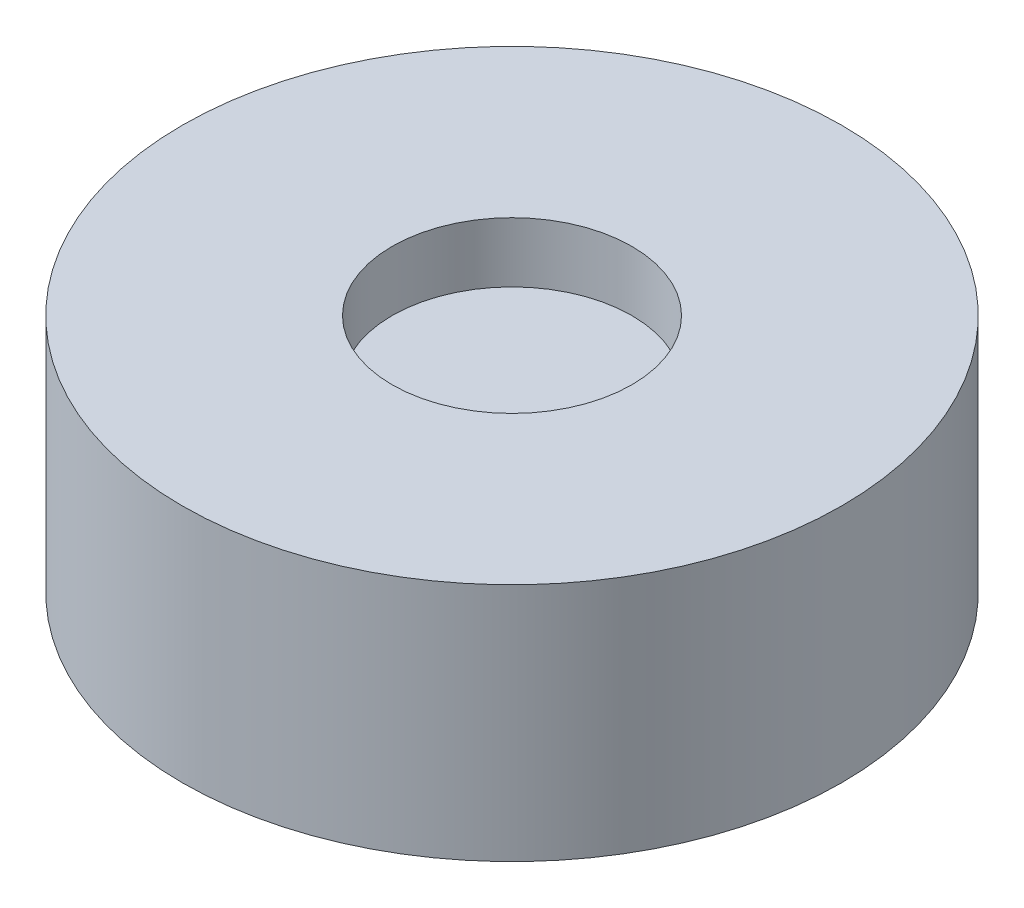
SolidWorks part; units mm, degrees
ref_plane "Front Plane" through (0, 0, 0) normal (0, 0, 1) x (1, 0, 0)
ref_plane "Top Plane" through (0, 0, 0) normal (0, 1, 0) x (1, 0, 0)
ref_plane "Right Plane" through (0, 0, 0) normal (1, 0, 0) x (0, 0, -1)
sketch "Sketch1" plane through (0, 0, 0) normal (0, 1, 0) x (1, 0, 0)
  circle A0 centre (0, 0) radius 4.15
  circle A1 centre (0, 0) radius 5.5
  dimension "D1" = 8.3
  dimension "D2" = 11
extrude "Boss-Extrude1" add sketch "Sketch1" along normal blind 3
sketch "Sketch2" plane through (0, 3, 0) normal (0, 1, 0) x (1, 0, 0)
  circle A0 centre (0, 0) radius 2
  circle A1 centre (0, 0) radius 5.5
  circle A2 centre (0, 0) radius 5.5
  dimension "D2" = 4
  dimension "D1" = 0
extrude "Boss-Extrude2" add sketch "Sketch2" along normal blind 1
sketch "Sketch3" plane through (0, 3, 0) normal (0, -1, 0) x (1, 0, 0)
  circle A1 centre (0, 0) radius 4.15
  circle A2 centre (0, 0) radius 4.15
  dimension "D1" = 0
extrude "Boss-Extrude3" add sketch "Sketch3" along normal blind 1
